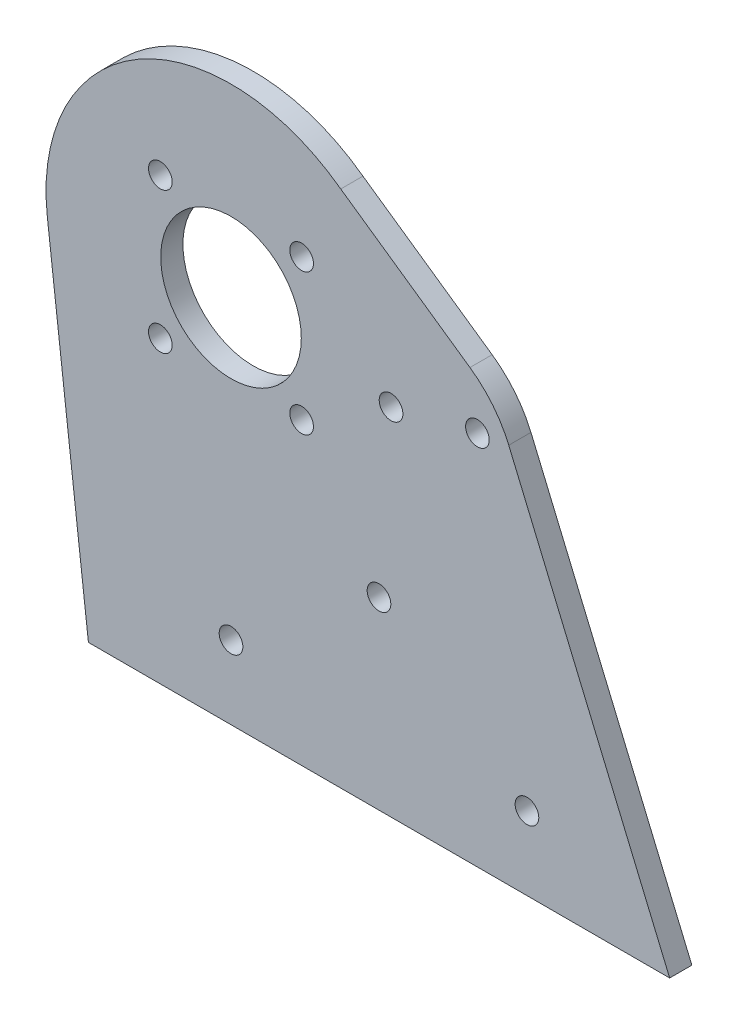
SolidWorks part; units mm, degrees
ref_plane "前视基准面" through (0, 0, 0) normal (0, 0, 1) x (1, 0, 0)
ref_plane "上视基准面" through (0, 0, 0) normal (0, 1, 0) x (1, 0, 0)
ref_plane "右视基准面" through (0, 0, 0) normal (1, 0, 0) x (0, 0, -1)
sketch "草图1" plane through (0, 0, 0) normal (0, 0, 1) x (1, 0, 0)
  line L0 (-34.3697, 8.1115) -> (-28.8138, -38.9579)
  line L1 (-28.8138, -38.9579) -> (49.7449, -38.9579)
  line L2 (27.9968, 12.5309) -> (49.7449, -38.9579)
  line L3 (22.7527, 19.0025) -> (5.29, 31.1669)
  circle A0 centre (-9.5421, 11.0421) radius 8
  arc A1 (5.29, 31.1669) -> (-34.3697, 8.1115) centre (-9.5421, 11.0421) ccw
  circle A2 centre (10.4579, -14.0427) radius 1.6
  circle A3 centre (30.4579, -29.0427) radius 1.6
  circle A4 centre (-9.5421, -29.0427) radius 1.6
  circle A5 centre (23.7628, 11.8216) radius 1.6
  circle A6 centre (12.0886, 9.0442) radius 1.6
  arc A7 (27.9968, 12.5309) -> (22.7527, 19.0025) centre (14.1789, 6.6944) ccw
  circle A8 centre (-9.5421, 11.0421) radius 8
  circle A9 centre (-9.5498, 11.0421) radius 13.5 construction
  circle A10 centre (0.0003, 20.5839) radius 1.6
  circle A11 centre (0, 1.5) radius 1.6
  circle A12 centre (-19.0916, 1.492) radius 1.6
  circle A13 centre (-19.0919, 20.5919) radius 1.6
  circle A14 centre (23.7628, 11.8216) radius 1.5
  dimension "D1" = 3.2
  dimension "D2" = 16
  dimension "D3" = 3.2
extrude "凸台-拉伸1" add sketch "草图1" along normal blind 3 contours L2 A7 L3 A1 L0 L1 A13 A12 A11 A10 A0 A2 A3 A4 A5 A6
sketch "草图2" plane through (0, 0, 3) normal (0, 0, 1) x (1, 0, 0)
  circle A0 centre (-9.5421, 11.0421) radius 9.5
  dimension "D1" = 19
extrude "切除-拉伸1" cut sketch "草图2" against normal blind 10
